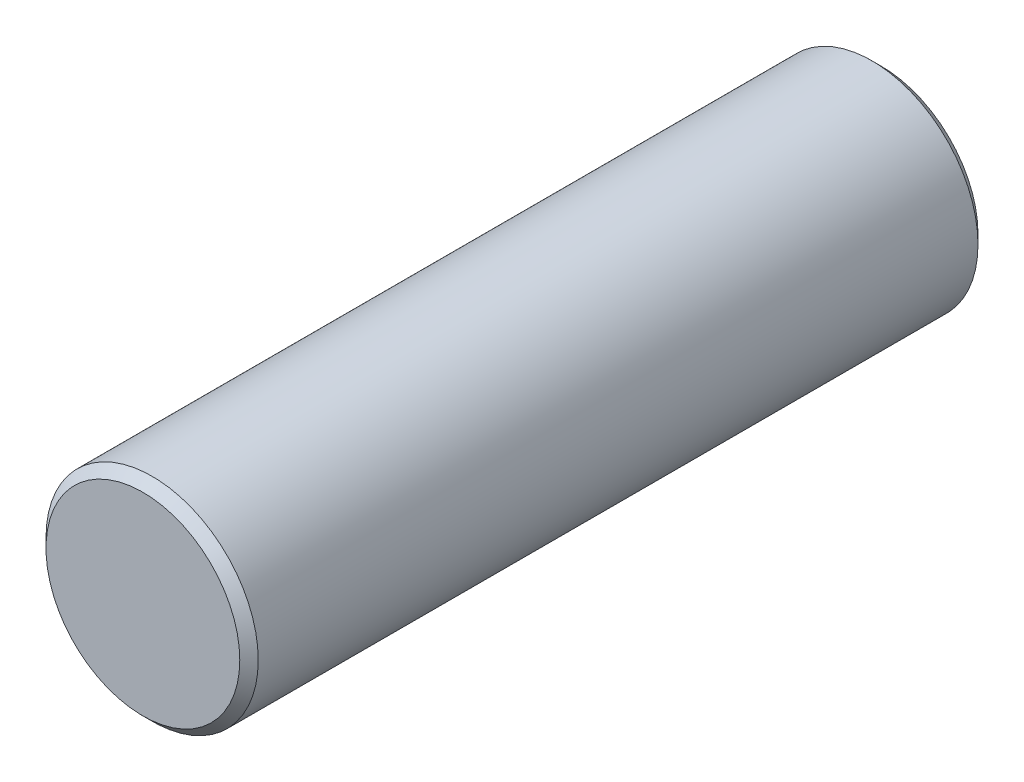
SolidWorks part; units mm, degrees
material "6061 Alloy"
ref_plane "Front Plane" through (0, 0, 0) normal (0, 0, 1) x (1, 0, 0)
ref_plane "Top Plane" through (0, 0, 0) normal (0, 1, 0) x (1, 0, 0)
ref_plane "Right Plane" through (0, 0, 0) normal (1, 0, 0) x (0, 0, -1)
sketch "Sketch2" plane through (0, 0, 0) normal (0, 0, 1) x (1, 0, 0)
  circle A0 centre (0, 0) radius 11.5
  dimension "D1" = 23
extrude "Boss-Extrude1" add sketch "Sketch2" along normal blind 80
chamfer "Chamfer1" distance 1 2 edges at (11.5, 0, 80) (11.5, 0, 0)
ref_plane "Plane1" through (0, -11.5, 0) normal (0, 1, 0) x (1, 0, 0)
sketch "Sketch4" plane through (0, -11.5, 0) normal (0, 1, 0) x (1, 0, 0)
  line L0 (0, 0) -> (0, -15) construction
  circle A0 centre (0, -15) radius 0.5
  point P2 (0, -15)
  dimension "D2" = 1
  dimension "D1" = 15
hole_wizard "M6x1.0 Tapped Hole1" positions "Sketch4" profile "Sketch5" tap size "M6x1.0" standard "ANSI Metric"
sketch "Sketch5" plane through (0, -11.5, 15) normal (1, 0, 0) x (0, 0, -1)
  line L0 (0, 0) -> (0, 13.0022)
  line L1 (0, 13.0022) -> (2.5, 11.5)
  line L2 (2.5, 11.5) -> (2.5, 0)
  line L5 (2.5, 0) -> (0, 0)
  line L10 (0, 13.0022) -> (-2.5, 11.5) construction
  line L11 (0, -6.35) -> (0, 107.95) construction
  dimension "Tap Drill Dia." = 5
  dimension "Tap Drill Depth" = 11.5
  dimension "Drill Angle" = 118
cosmetic thread "Hole Thread1" parameters "D1"=12, "D2"=6
